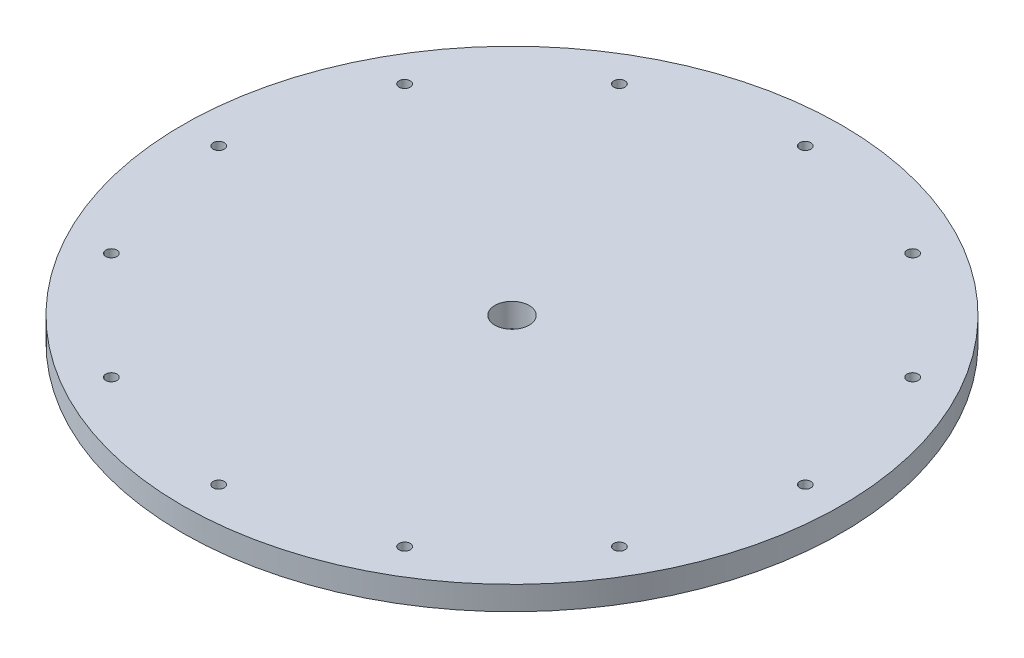
SolidWorks part; units mm, degrees
ref_plane "Front Plane" through (0, 0, 0) normal (0, 0, 1) x (1, 0, 0)
ref_plane "Top Plane" through (0, 0, 0) normal (0, 1, 0) x (1, 0, 0)
ref_plane "Right Plane" through (0, 0, 0) normal (1, 0, 0) x (0, 0, -1)
sketch "Sketch1" plane through (0, 0, 0) normal (0, 1, 0) x (1, 0, 0)
  line L0 (0, 281.8419) -> (0, -288.6827) construction
  line L1 (-394.0314, 0) -> (412.5016, 0) construction
  circle A0 centre (0, 0) radius 250
  circle A2 centre (0, 222.5) radius 4.25
  circle A3 centre (111.25, 192.6907) radius 4.25
  circle A4 centre (192.6907, 111.25) radius 4.25
  circle A5 centre (222.5, 0) radius 4.25
  circle A6 centre (192.6907, -111.25) radius 4.25
  circle A7 centre (111.25, -192.6907) radius 4.25
  circle A8 centre (0, 0) radius 222.5 construction
  circle A9 centre (0, 0) radius 13
  circle A10 centre (0, -222.5) radius 4.25
  circle A11 centre (-111.25, -192.6907) radius 4.25
  circle A12 centre (-192.6907, -111.25) radius 4.25
  circle A13 centre (-222.5, 0) radius 4.25
  circle A14 centre (-192.6907, 111.25) radius 4.25
  circle A15 centre (-111.25, 192.6907) radius 4.25
  point P22 (0, 0)
  dimension "D1" = 500
  dimension "D2" = 26
  dimension "D3" = 8.5
  dimension "D6" = 445
  dimension "D4" = 222.5
  dimension "D5" = 12
extrude "Boss-Extrude1" add sketch "Sketch1" along normal mid plane 18
